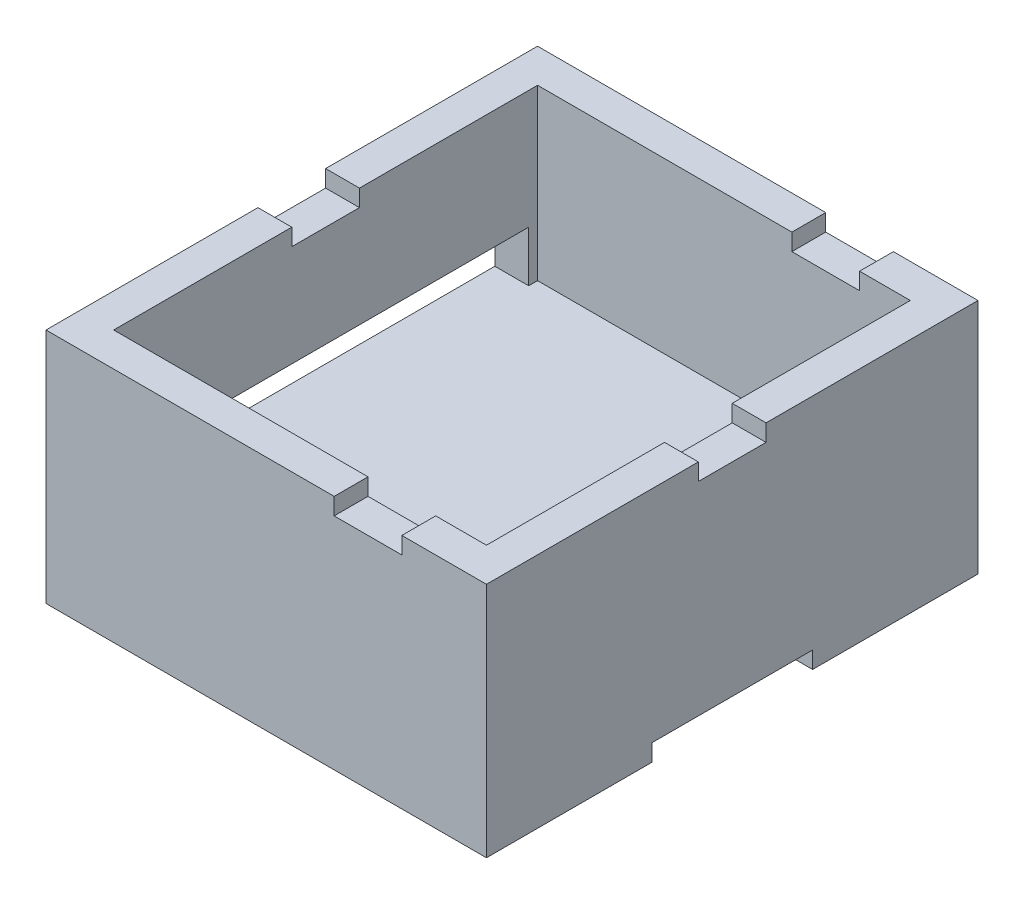
SolidWorks part; units mm, degrees
ref_plane "Front Plane" through (0, 0, 0) normal (0, 0, 1) x (1, 0, 0)
ref_plane "Top Plane" through (0, 0, 0) normal (0, 1, 0) x (1, 0, 0)
ref_plane "Right Plane" through (0, 0, 0) normal (1, 0, 0) x (0, 0, -1)
sketch "Sketch1" plane through (0, 0, 0) normal (0, 1, 0) x (1, 0, 0)
  line L14 (20.53, 23.55) -> (-1.5, 23.55)
  line L15 (-1.5, 23.55) -> (-1.5, -1.5)
  line L16 (-1.5, -1.5) -> (20.53, -1.5)
  line L17 (20.53, -1.5) -> (20.53, 23.55)
  circle A0 centre (16.53, 2.5) radius 1.5
  circle A1 centre (16.53, 19.55) radius 1.5
extrude "Boss-Extrude1" add sketch "Sketch1" along normal blind 4
sketch "Sketch2" plane through (0, 0, 0) normal (0, -1, 0) x (1, 0, 0)
  line L0 (-1.5, 1.5) -> (20.53, 1.5)
  line L1 (20.53, 1.5) -> (20.53, -23.55)
  line L2 (20.53, -23.55) -> (-1.5, -23.55)
  line L3 (-1.5, -23.55) -> (-1.5, 1.5)
  line L8 (-3.5, -25.55) -> (-3.5, 3.5)
  line L9 (-3.5, 3.5) -> (22.53, 3.5)
  line L10 (22.53, 3.5) -> (22.53, -25.55)
  line L11 (22.53, -25.55) -> (-3.5, -25.55)
extrude "Boss-Extrude3" add sketch "Sketch2" against normal blind 14
sketch "Sketch3" plane through (-3.5, 0, 0) normal (-1, 0, 0) x (0, 0, 1)
  line L2 (-11.025, 4) -> (-23.025, 4)
  line L3 (-11.025, 4) -> (0.975, 4)
  line L4 (-23.025, 4) -> (-23.025, 7)
  line L5 (-23.025, 7) -> (0.975, 7)
  line L6 (0.975, 7) -> (0.975, 4)
extrude "Cut-Extrude1" cut sketch "Sketch3" against normal blind 5
sketch "Sketch4" plane through (-3.5, 0, 0) normal (-1, 0, 0) x (0, 0, 1)
  line L0 (-11.025, 14) -> (-13.025, 14)
  line L1 (3.5, 14) -> (-25.55, 14) construction
  line L2 (-11.025, 14) -> (-9.025, 14)
  line L3 (-13.025, 14) -> (-13.025, 13)
  line L4 (-13.025, 13) -> (-9.025, 13)
  line L5 (-9.025, 13) -> (-9.025, 14)
extrude "Cut-Extrude2" cut sketch "Sketch4" against normal blind 50
sketch "Sketch5" plane through (0, 0, -25.55) normal (0, 0, -1) x (-1, 0, 0)
  line L1 (3.5, 14) -> (-22.53, 14) construction
  line L2 (-17.53, 14) -> (-13.53, 14)
  line L3 (-13.53, 14) -> (-13.53, 13)
  line L4 (-13.53, 13) -> (-17.53, 13)
  line L5 (-17.53, 13) -> (-17.53, 14)
extrude "Cut-Extrude3" cut sketch "Sketch5" against normal blind 50
ref_plane "Plane1" through (13.53, 13, 3.5) normal (0, -1, 0) x (-1, 0, 0)
sketch "Sketch7" plane through (0, 0, 0) normal (0, -1, 0) x (1, 0, 0)
  line L0 (-3.5, -11.025) -> (-3.5, -6.275)
  line L1 (-3.5, 3.5) -> (-3.5, -25.55) construction
  line L2 (-3.5, -11.025) -> (-3.5, -15.775)
  line L3 (-3.5, -6.275) -> (22.53, -6.275)
  line L4 (22.53, -25.55) -> (22.53, 3.5) construction
  line L5 (22.53, -6.275) -> (22.53, -15.775)
  line L6 (22.53, -15.775) -> (-3.5, -15.775)
extrude "Cut-Extrude4" cut sketch "Sketch7" against normal blind 1
